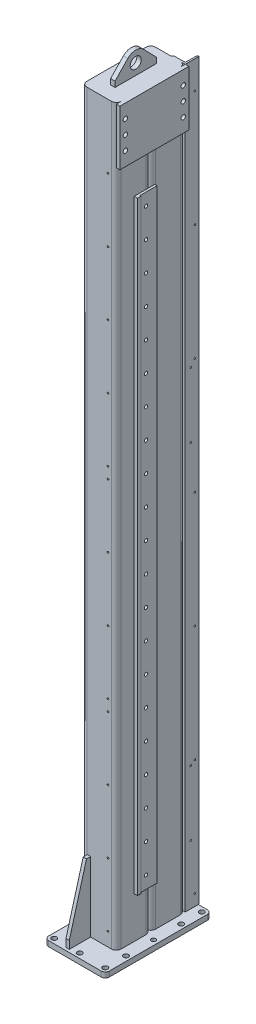
SolidWorks part; units mm, degrees
ref_plane "正面" through (0, 0, 0) normal (0, 0, 1) x (1, 0, 0)
ref_plane "平面" through (0, 0, 0) normal (0, 1, 0) x (1, 0, 0)
ref_plane "右側面" through (0, 0, 0) normal (1, 0, 0) x (0, 0, -1)
ref_plane "平面1" through (0, 19, 0) normal (0, 1, 0) x (1, 0, 0)
sketch "ｽｹｯﾁ2" plane through (0, 19, 0) normal (0, 1, 0) x (1, 0, 0)
  line L0 (-44.5, -105) -> (44.5, -105)
  line L1 (62.5, -87) -> (62.5, 2)
  line L2 (44.5, 20) -> (-44.5, 20)
  line L3 (-62.5, 2) -> (-62.5, -87)
  arc A0 (44.5, -105) -> (62.5, -87) centre (44.5, -87) ccw
  arc A1 (62.5, 2) -> (44.5, 20) centre (44.5, 2) ccw
  arc A2 (-44.5, 20) -> (-62.5, 2) centre (-44.5, 2) ccw
  arc A3 (-62.5, -87) -> (-44.5, -105) centre (-44.5, -87) ccw
extrude "ﾎﾞｽ - 押し出し1" add sketch "ｽｹｯﾁ2" along normal blind 2643
sketch "ｽｹｯﾁ3" plane through (0, 19, 0) normal (0, 1, 0) x (1, 0, 0)
  line L0 (-44.5, 20) -> (44.5, 20)
  line L1 (62.5, 38) -> (62.5, 127)
  line L2 (44.5, 145) -> (-44.5, 145)
  line L3 (-62.5, 127) -> (-62.5, 38)
  arc A0 (44.5, 20) -> (62.5, 38) centre (44.5, 38) ccw
  arc A1 (62.5, 127) -> (44.5, 145) centre (44.5, 127) ccw
  arc A2 (-44.5, 145) -> (-62.5, 127) centre (-44.5, 127) ccw
  arc A3 (-62.5, 38) -> (-44.5, 20) centre (-44.5, 38) ccw
extrude "ﾎﾞｽ - 押し出し2" add sketch "ｽｹｯﾁ3" along normal blind 2643
sketch "ｽｹｯﾁ4" plane through (0, 19, 0) normal (0, 1, 0) x (1, 0, 0)
  line L0 (-44.5, -96) -> (44.5, -96)
  line L1 (53.5, -87) -> (53.5, 2)
  line L2 (44.5, 11) -> (-44.5, 11)
  line L3 (-53.5, 2) -> (-53.5, -87)
  line L4 (-44.5, 29) -> (44.5, 29)
  line L5 (53.5, 38) -> (53.5, 127)
  line L6 (44.5, 136) -> (-44.5, 136)
  line L7 (-53.5, 127) -> (-53.5, 38)
  arc A0 (44.5, -96) -> (53.5, -87) centre (44.5, -87) ccw
  arc A1 (53.5, 2) -> (44.5, 11) centre (44.5, 2) ccw
  arc A2 (-44.5, 11) -> (-53.5, 2) centre (-44.5, 2) ccw
  arc A3 (-53.5, -87) -> (-44.5, -96) centre (-44.5, -87) ccw
  arc A4 (44.5, 29) -> (53.5, 38) centre (44.5, 38) ccw
  arc A5 (53.5, 127) -> (44.5, 136) centre (44.5, 127) ccw
  arc A6 (-44.5, 136) -> (-53.5, 127) centre (-44.5, 127) ccw
  arc A7 (-53.5, 38) -> (-44.5, 29) centre (-44.5, 38) ccw
extrude "ｶｯﾄ - 押し出し1" cut sketch "ｽｹｯﾁ4" against normal through all and the other way through all
sketch "ｽｹｯﾁ5" plane through (0, 0, 0) normal (0, 1, 0) x (1, 0, 0)
  line L0 (-95, -192.5) -> (95, -192.5)
  line L1 (110, -177.5) -> (110, 177.5)
  line L2 (95, 192.5) -> (-95, 192.5)
  line L3 (-110, 177.5) -> (-110, -177.5)
  arc A0 (95, -192.5) -> (110, -177.5) centre (95, -177.5) ccw
  arc A1 (110, 177.5) -> (95, 192.5) centre (95, 177.5) ccw
  arc A2 (-95, 192.5) -> (-110, 177.5) centre (-95, 177.5) ccw
  arc A3 (-110, -177.5) -> (-95, -192.5) centre (-95, -177.5) ccw
extrude "ﾎﾞｽ - 押し出し3" add sketch "ｽｹｯﾁ5" along normal blind 19
ref_plane "平面2" through (-42.5, 0, 0) normal (1, 0, 0) x (0, 0, -1)
sketch "ｽｹｯﾁ7" plane through (-42.5, 0, 0) normal (1, 0, 0) x (0, 0, -1)
  line L0 (-105, 19) -> (-105, 272)
  line L1 (-105, 272) -> (-120, 272)
  line L2 (-120, 272) -> (-182.5, 47)
  line L3 (-182.5, 47) -> (-182.5, 19)
  line L4 (-182.5, 19) -> (-105, 19)
extrude "ﾎﾞｽ - 押し出し4" add sketch "ｽｹｯﾁ7" along normal blind 12
sketch "ｽｹｯﾁ8" plane through (0, 19, 0) normal (0, 1, 0) x (1, 0, 0)
  line L0 (62.5, 145) -> (12.5, 145)
  line L1 (12.5, 145) -> (12.5, 147)
  line L2 (16.5, 151) -> (50.5, 151)
  line L3 (56.5, 157) -> (56.5, 191)
  line L4 (60.5, 195) -> (62.5, 195)
  line L5 (62.5, 195) -> (62.5, 145)
  arc A0 (12.5, 147) -> (16.5, 151) centre (16.5, 147) cw
  arc A1 (50.5, 151) -> (56.5, 157) centre (50.5, 157) ccw
  arc A2 (56.5, 191) -> (60.5, 195) centre (60.5, 191) cw
extrude "ﾎﾞｽ - 押し出し5" add sketch "ｽｹｯﾁ8" along normal blind 2662
ref_plane "平面3" through (0, 169, 0) normal (0, 1, 0) x (1, 0, 0)
sketch "ｽｹｯﾁ10" plane through (0, 169, 0) normal (0, 1, 0) x (1, 0, 0)
  line L0 (62.5, -40) -> (74.5, -40)
  line L1 (74.5, -40) -> (74.5, -27.5)
  line L2 (74.5, -27.5) -> (70.5, -27.5)
  line L3 (70.5, -27.5) -> (70.5, 35)
  line L4 (70.5, 35) -> (62.5, 35)
  line L5 (62.5, 35) -> (62.5, -40)
extrude "ﾎﾞｽ - 押し出し6" add sketch "ｽｹｯﾁ10" along normal blind 2190
ref_plane "平面4" through (0, 2662, 0) normal (0, 1, 0) x (1, 0, 0)
sketch "ｽｹｯﾁ12" plane through (0, 2662, 0) normal (0, 1, 0) x (1, 0, 0)
  line L0 (-44.5, -105) -> (44.5, -105)
  line L1 (62.5, -87) -> (62.5, 127)
  line L2 (44.5, 145) -> (-44.5, 145)
  line L3 (-62.5, 127) -> (-62.5, -87)
  arc A0 (44.5, -105) -> (62.5, -87) centre (44.5, -87) ccw
  arc A1 (62.5, 127) -> (44.5, 145) centre (44.5, 127) ccw
  arc A2 (-44.5, 145) -> (-62.5, 127) centre (-44.5, 127) ccw
  arc A3 (-62.5, -87) -> (-44.5, -105) centre (-44.5, -87) ccw
extrude "ﾎﾞｽ - 押し出し7" add sketch "ｽｹｯﾁ12" along normal blind 19
ref_plane "平面5" through (62.5, 0, 0) normal (1, 0, 0) x (0, 0, -1)
sketch "ｽｹｯﾁ14" plane through (62.5, 0, 0) normal (1, 0, 0) x (0, 0, -1)
  line L0 (-105, 2481) -> (144.98, 2481)
  line L1 (144.98, 2481) -> (144.98, 2681)
  line L2 (144.98, 2681) -> (-105, 2681)
  line L3 (-105, 2681) -> (-105, 2481)
extrude "ﾎﾞｽ - 押し出し8" add sketch "ｽｹｯﾁ14" along normal blind 13
sketch "ｽｹｯﾁ15" plane through (0, 0, 0) normal (1, 0, 0) x (0, 0, -1)
  line L0 (-55, 2681) -> (95, 2681)
  line L1 (95, 2681) -> (95, 2701)
  line L2 (95, 2701) -> (48.7496, 2748.8111)
  line L3 (-8.7496, 2748.8111) -> (-55, 2701)
  line L4 (-55, 2701) -> (-55, 2681)
  arc A0 (48.7496, 2748.8111) -> (-8.7496, 2748.8111) centre (20, 2721) ccw
extrude "ﾎﾞｽ - 押し出し9" add sketch "ｽｹｯﾁ15" against normal blind 8 and the other way blind 8
sketch "ｽｹｯﾁ16" plane through (0, 0, 0) normal (0, 1, 0) x (1, 0, 0)
  circle A0 centre (-92.5, -175) radius 9
  circle A1 centre (0, -175) radius 9
  circle A2 centre (92.5, -175) radius 9
  circle A3 centre (-92.5, -100) radius 9
  circle A4 centre (92.5, -100) radius 9
  circle A5 centre (-92.5, 100) radius 9
  circle A6 centre (92.5, 100) radius 9
  circle A7 centre (-92.5, 175) radius 9
  circle A8 centre (0, 175) radius 9
  circle A9 centre (92.5, 175) radius 9
sketch "ｽｹｯﾁ17" plane through (0, 0, 0) normal (0, 1, 0) x (1, 0, 0)
  circle A0 centre (-92.5, -175) radius 9
  circle A1 centre (0, -175) radius 9
  circle A2 centre (92.5, -175) radius 9
  circle A3 centre (-92.5, -100) radius 9
  circle A4 centre (92.5, -100) radius 9
  circle A5 centre (-92.5, 100) radius 9
  circle A6 centre (92.5, 100) radius 9
  circle A7 centre (-92.5, 175) radius 9
  circle A8 centre (0, 175) radius 9
  circle A9 centre (92.5, 175) radius 9
extrude "ｶｯﾄ - 押し出し3" cut sketch "ｽｹｯﾁ17" along normal blind 19
sketch "ｽｹｯﾁ18" plane through (0, 0, 0) normal (0, 1, 0) x (1, 0, 0)
  circle A0 centre (-92.5, 0) radius 8
  circle A1 centre (92.5, 0) radius 8
sketch "ｽｹｯﾁ19" plane through (0, 0, 0) normal (0, 1, 0) x (1, 0, 0)
  circle A0 centre (-92.5, 0) radius 8
  circle A1 centre (92.5, 0) radius 8
extrude "ｶｯﾄ - 押し出し5" cut sketch "ｽｹｯﾁ19" along normal blind 19
sketch "ｽｹｯﾁ20" plane through (0, 0, 0) normal (1, 0, 0) x (0, 0, -1)
  circle A0 centre (-85, 2531) radius 8
  circle A1 centre (125, 2531) radius 8
  circle A2 centre (-85, 2631) radius 8
  circle A3 centre (125, 2631) radius 8
sketch "ｽｹｯﾁ21" plane through (0, 0, 0) normal (1, 0, 0) x (0, 0, -1)
  circle A0 centre (-85, 2531) radius 8
  circle A1 centre (125, 2531) radius 8
  circle A2 centre (-85, 2631) radius 8
  circle A3 centre (125, 2631) radius 8
sketch "ｽｹｯﾁ22" plane through (0, 0, 0) normal (1, 0, 0) x (0, 0, -1)
  circle A0 centre (-2531, -85) radius 8
sketch "ｽｹｯﾁ23" plane through (0, 0, 0) normal (1, 0, 0) x (0, 0, -1)
  circle A0 centre (-2531, -85) radius 8
sketch "ｽｹｯﾁ24" plane through (0, 0, 0) normal (1, 0, 0) x (0, 0, -1)
  circle A0 centre (-2531, -70) radius 8
sketch "ｽｹｯﾁ25" plane through (0, 0, 0) normal (1, 0, 0) x (0, 0, -1)
  circle A0 centre (-2531, -70) radius 8
sketch "ｽｹｯﾁ26" plane through (0, 0, 0) normal (1, 0, 0) x (0, 0, -1)
  circle A0 centre (-2531, 125) radius 8
sketch "ｽｹｯﾁ27" plane through (0, 0, 0) normal (1, 0, 0) x (0, 0, -1)
  circle A0 centre (-2531, 110) radius 8
sketch "ｽｹｯﾁ28" plane through (0, 0, 0) normal (1, 0, 0) x (0, 0, -1)
  circle A0 centre (-2531, -85) radius 8
  circle A1 centre (-2531, 125) radius 8
  circle A2 centre (-2631, -85) radius 8
  circle A3 centre (-2631, 125) radius 8
sketch "ｽｹｯﾁ29" plane through (0, 0, 0) normal (1, 0, 0) x (0, 0, -1)
  circle A0 centre (-2531, -70) radius 8
sketch "ｽｹｯﾁ30" plane through (0, 0, 0) normal (1, 0, 0) x (0, 0, -1)
  circle A0 centre (-2531, -70) radius 8
sketch "ｽｹｯﾁ31" plane through (0, 0, 0) normal (1, 0, 0) x (0, 0, -1)
  circle A0 centre (-2531, -70) radius 8
sketch "ｽｹｯﾁ32" plane through (0, 0, 0) normal (1, 0, 0) x (0, 0, -1)
  circle A0 centre (-2531, -70) radius 8
sketch "ｽｹｯﾁ33" plane through (0, 0, 0) normal (1, 0, 0) x (0, 0, -1)
  circle A0 centre (-2531, -70) radius 8
sketch "ｽｹｯﾁ34" plane through (0, 0, 0) normal (1, 0, 0) x (0, 0, -1)
  circle A0 centre (-2531, -70) radius 8
sketch "ｽｹｯﾁ35" plane through (0, 0, 0) normal (1, 0, 0) x (0, 0, -1)
  circle A0 centre (-2531, -85) radius 8
sketch "ｽｹｯﾁ36" plane through (0, 0, 0) normal (1, 0, 0) x (0, 0, -1)
  circle A0 centre (-2531, -85) radius 8
sketch "ｽｹｯﾁ37" plane through (0, 0, 0) normal (1, 0, 0) x (0, 0, -1)
  circle A0 centre (-2531, -85) radius 8
sketch "ｽｹｯﾁ38" plane through (0, 0, 0) normal (1, 0, 0) x (0, 0, -1)
  circle A0 centre (-2531, -85) radius 8
sketch "ｽｹｯﾁ39" plane through (0, 0, 0) normal (1, 0, 0) x (0, 0, -1)
  circle A0 centre (-2531, 125) radius 8
sketch "ｽｹｯﾁ40" plane through (0, 0, 0) normal (1, 0, 0) x (0, 0, -1)
  circle A0 centre (-2531, 125) radius 8
sketch "ｽｹｯﾁ41" plane through (0, 0, 0) normal (1, 0, 0) x (0, 0, -1)
  circle A0 centre (-2531, 110) radius 8
sketch "ｽｹｯﾁ42" plane through (0, 0, 0) normal (1, 0, 0) x (0, 0, -1)
  circle A0 centre (-2531, 110) radius 8
sketch "ｽｹｯﾁ43" plane through (0, 0, 0) normal (1, 0, 0) x (0, 0, -1)
  circle A0 centre (-2531, -85) radius 8
  circle A1 centre (-2531, 125) radius 8
  circle A2 centre (-2631, -85) radius 8
  circle A3 centre (-2631, 125) radius 8
sketch "ｽｹｯﾁ44" plane through (0, 0, 0) normal (1, 0, 0) x (0, 0, -1)
  circle A0 centre (-2531, -70) radius 8
sketch "ｽｹｯﾁ45" plane through (0, 0, 0) normal (1, 0, 0) x (0, 0, -1)
  circle A0 centre (-70, 2531) radius 8
sketch "ｽｹｯﾁ46" plane through (0, 0, 0) normal (1, 0, 0) x (0, 0, -1)
  circle A0 centre (-70, 2531) radius 8
sketch "ｽｹｯﾁ47" plane through (0, 0, 0) normal (1, 0, 0) x (0, 0, -1)
  circle A0 centre (110, 2531) radius 8
sketch "ｽｹｯﾁ48" plane through (0, 0, 0) normal (1, 0, 0) x (0, 0, -1)
  circle A0 centre (-85, 2531) radius 8
sketch "ｽｹｯﾁ49" plane through (0, 0, 0) normal (1, 0, 0) x (0, 0, -1)
  circle A0 centre (-85, 2531) radius 8
sketch "ｽｹｯﾁ50" plane through (0, 0, 0) normal (1, 0, 0) x (0, 0, -1)
  circle A0 centre (125, 2531) radius 8
sketch "ｽｹｯﾁ51" plane through (0, 0, 0) normal (1, 0, 0) x (0, 0, -1)
  circle A0 centre (-95, 2531) radius 1
sketch "ｽｹｯﾁ52" plane through (0, 0, 0) normal (1, 0, 0) x (0, 0, -1)
  circle A0 centre (-93, 2531) radius 1
sketch "ｽｹｯﾁ53" plane through (0, 0, 0) normal (1, 0, 0) x (0, 0, -1)
  circle A0 centre (-91, 2531) radius 1
sketch "ｽｹｯﾁ54" plane through (0, 0, 0) normal (1, 0, 0) x (0, 0, -1)
  circle A0 centre (-89, 2531) radius 1
sketch "ｽｹｯﾁ55" plane through (0, 0, 0) normal (1, 0, 0) x (0, 0, -1)
  circle A0 centre (-87, 2531) radius 1
sketch "ｽｹｯﾁ56" plane through (0, 0, 0) normal (1, 0, 0) x (0, 0, -1)
  circle A0 centre (-85, 2531) radius 1
sketch "ｽｹｯﾁ57" plane through (0, 0, 0) normal (1, 0, 0) x (0, 0, -1)
  circle A0 centre (-83, 2531) radius 1
sketch "ｽｹｯﾁ58" plane through (0, 0, 0) normal (1, 0, 0) x (0, 0, -1)
  circle A0 centre (-80, 2531) radius 1
sketch "ｽｹｯﾁ59" plane through (0, 0, 0) normal (1, 0, 0) x (0, 0, -1)
  circle A0 centre (80, 2531) radius 1
sketch "ｽｹｯﾁ60" plane through (0, 0, 0) normal (1, 0, 0) x (0, 0, -1)
  circle A0 centre (127, 2531) radius 1
sketch "ｽｹｯﾁ61" plane through (0, 0, 0) normal (1, 0, 0) x (0, 0, -1)
  circle A0 centre (129, 2531) radius 1
sketch "ｽｹｯﾁ62" plane through (0, 0, 0) normal (1, 0, 0) x (0, 0, -1)
  circle A0 centre (131, 2531) radius 1
sketch "ｽｹｯﾁ63" plane through (0, 0, 0) normal (1, 0, 0) x (0, 0, -1)
  circle A0 centre (133, 2531) radius 1
sketch "ｽｹｯﾁ64" plane through (0, 0, 0) normal (1, 0, 0) x (0, 0, -1)
  circle A0 centre (135, 2531) radius 1
sketch "ｽｹｯﾁ65" plane through (0, 0, 0) normal (1, 0, 0) x (0, 0, -1)
  circle A0 centre (-85, 2531) radius 8
sketch "ｽｹｯﾁ66" plane through (0, 0, 0) normal (1, 0, 0) x (0, 0, -1)
  circle A0 centre (-85, 2531) radius 8
sketch "ｽｹｯﾁ67" plane through (0, 0, 0) normal (1, 0, 0) x (0, 0, -1)
  circle A0 centre (-85, 2531) radius 8
sketch "ｽｹｯﾁ68" plane through (0, 0, 0) normal (1, 0, 0) x (0, 0, -1)
  circle A0 centre (-85, 2531) radius 8
  circle A1 centre (125, 2531) radius 8
  circle A2 centre (-85, 2631) radius 8
  circle A3 centre (125, 2631) radius 8
sketch "ｽｹｯﾁ69" plane through (0, 0, 0) normal (1, 0, 0) x (0, 0, -1)
  circle A0 centre (-85, 2531) radius 8
  circle A1 centre (125, 2531) radius 8
  circle A2 centre (-85, 2631) radius 8
  circle A3 centre (125, 2631) radius 8
extrude "ｶｯﾄ - 押し出し54" cut sketch "ｽｹｯﾁ69" along normal blind 75.5
sketch "ｽｹｯﾁ70" plane through (0, 0, 0) normal (1, 0, 0) x (0, 0, -1)
  circle A0 centre (-85, 2581) radius 8
  circle A1 centre (125, 2581) radius 8
sketch "ｽｹｯﾁ71" plane through (0, 0, 0) normal (1, 0, 0) x (0, 0, -1)
  circle A0 centre (-85, 2581) radius 8
  circle A1 centre (125, 2581) radius 8
extrude "ｶｯﾄ - 押し出し56" cut sketch "ｽｹｯﾁ71" along normal blind 75.5
sketch "ｽｹｯﾁ72" plane through (0, 0, 0) normal (1, 0, 0) x (0, 0, -1)
  circle A0 centre (-5, 214.5) radius 6
  circle A1 centre (-5, 319.5) radius 6
  circle A2 centre (-5, 424.5) radius 6
  circle A3 centre (-5, 529.5) radius 6
  circle A4 centre (-5, 634.5) radius 6
  circle A5 centre (-5, 739.5) radius 6
  circle A6 centre (-5, 844.5) radius 6
  circle A7 centre (-5, 949.5) radius 6
  circle A8 centre (-5, 1054.5) radius 6
  circle A9 centre (-5, 1159.5) radius 6
  circle A10 centre (-5, 1264.5) radius 6
  circle A11 centre (-5, 1369.5) radius 6
  circle A12 centre (-5, 1474.5) radius 6
  circle A13 centre (-5, 1579.5) radius 6
  circle A14 centre (-5, 1684.5) radius 6
  circle A15 centre (-5, 1789.5) radius 6
  circle A16 centre (-5, 1894.5) radius 6
  circle A17 centre (-5, 1999.5) radius 6
  circle A18 centre (-5, 2104.5) radius 6
  circle A19 centre (-5, 2209.5) radius 6
  circle A20 centre (-5, 2314.5) radius 6
sketch "ｽｹｯﾁ73" plane through (0, 0, 0) normal (1, 0, 0) x (0, 0, -1)
  circle A0 centre (-5, 214.5) radius 6
  circle A1 centre (-5, 319.5) radius 6
  circle A2 centre (-5, 424.5) radius 6
  circle A3 centre (-5, 529.5) radius 6
  circle A4 centre (-5, 634.5) radius 6
  circle A5 centre (-5, 739.5) radius 6
  circle A6 centre (-5, 844.5) radius 6
  circle A7 centre (-5, 949.5) radius 6
  circle A8 centre (-5, 1054.5) radius 6
  circle A9 centre (-5, 1159.5) radius 6
  circle A10 centre (-5, 1264.5) radius 6
  circle A11 centre (-5, 1369.5) radius 6
  circle A12 centre (-5, 1474.5) radius 6
  circle A13 centre (-5, 1579.5) radius 6
  circle A14 centre (-5, 1684.5) radius 6
  circle A15 centre (-5, 1789.5) radius 6
  circle A16 centre (-5, 1894.5) radius 6
  circle A17 centre (-5, 1999.5) radius 6
  circle A18 centre (-5, 2104.5) radius 6
  circle A19 centre (-5, 2209.5) radius 6
  circle A20 centre (-5, 2314.5) radius 6
extrude "ｶｯﾄ - 押し出し58" cut sketch "ｽｹｯﾁ73" along normal blind 70.5
sketch "ｽｹｯﾁ74" plane through (0, 0, 0) normal (0, 0, 1) x (1, 0, 0)
  circle A0 centre (32.5, 2448.5) radius 3
  circle A1 centre (32.5, 2218.5) radius 3
  circle A2 centre (32.5, 1988.5) radius 3
  circle A3 centre (32.5, 1758.5) radius 3
  circle A4 centre (32.5, 1528.5) radius 3
  circle A5 centre (32.5, 1488.5) radius 3
  circle A6 centre (32.5, 1258.5) radius 3
  circle A7 centre (32.5, 1028.5) radius 3
  circle A8 centre (32.5, 798.5) radius 3
  circle A9 centre (32.5, 758.5) radius 3
  circle A10 centre (32.5, 528.5) radius 3
  circle A11 centre (32.5, 298.5) radius 3
  circle A12 centre (32.5, 68.5) radius 3
sketch "ｽｹｯﾁ75" plane through (0, 0, 0) normal (0, 0, 1) x (1, 0, 0)
  circle A0 centre (32.5, 2448.5) radius 3
  circle A1 centre (32.5, 2218.5) radius 3
  circle A2 centre (32.5, 1988.5) radius 3
  circle A3 centre (32.5, 1758.5) radius 3
  circle A4 centre (32.5, 1528.5) radius 3
  circle A5 centre (32.5, 1488.5) radius 3
  circle A6 centre (32.5, 1258.5) radius 3
  circle A7 centre (32.5, 1028.5) radius 3
  circle A8 centre (32.5, 798.5) radius 3
  circle A9 centre (32.5, 758.5) radius 3
  circle A10 centre (32.5, 528.5) radius 3
  circle A11 centre (32.5, 298.5) radius 3
  circle A12 centre (32.5, 68.5) radius 3
extrude "ｶｯﾄ - 押し出し60" cut sketch "ｽｹｯﾁ75" along normal blind 105
sketch "ｽｹｯﾁ76" plane through (0, 0, 0) normal (1, 0, 0) x (0, 0, -1)
  circle A0 centre (180, 60) radius 3
  circle A1 centre (180, 480) radius 3
  circle A2 centre (180, 900) radius 3
  circle A3 centre (180, 1320) radius 3
  circle A4 centre (180, 1740) radius 3
  circle A5 centre (180, 2160) radius 3
  circle A6 centre (180, 2580) radius 3
sketch "ｽｹｯﾁ77" plane through (0, 0, 0) normal (1, 0, 0) x (0, 0, -1)
  circle A0 centre (180, 60) radius 3
  circle A1 centre (180, 480) radius 3
  circle A2 centre (180, 900) radius 3
  circle A3 centre (180, 1320) radius 3
  circle A4 centre (180, 1740) radius 3
  circle A5 centre (180, 2160) radius 3
  circle A6 centre (180, 2580) radius 3
extrude "ｶｯﾄ - 押し出し62" cut sketch "ｽｹｯﾁ77" along normal blind 62.5
sketch "ｽｹｯﾁ78" plane through (0, 0, 0) normal (1, 0, 0) x (0, 0, -1)
  circle A0 centre (165, 1718.5) radius 3
  circle A1 centre (165, 1483.5) radius 3
  circle A2 centre (165, 468.5) radius 3
  circle A3 centre (165, 233.5) radius 3
sketch "ｽｹｯﾁ79" plane through (0, 0, 0) normal (1, 0, 0) x (0, 0, -1)
  circle A0 centre (165, 1718.5) radius 3
  circle A1 centre (165, 1483.5) radius 3
  circle A2 centre (165, 468.5) radius 3
  circle A3 centre (165, 233.5) radius 3
extrude "ｶｯﾄ - 押し出し64" cut sketch "ｽｹｯﾁ79" along normal blind 62.5
sketch "ｽｹｯﾁ80" plane through (0, 0, 0) normal (1, 0, 0) x (0, 0, -1)
  circle A0 centre (20, 2721) radius 20
extrude "ｶｯﾄ - 押し出し65" cut sketch "ｽｹｯﾁ80" against normal through all and the other way through all
